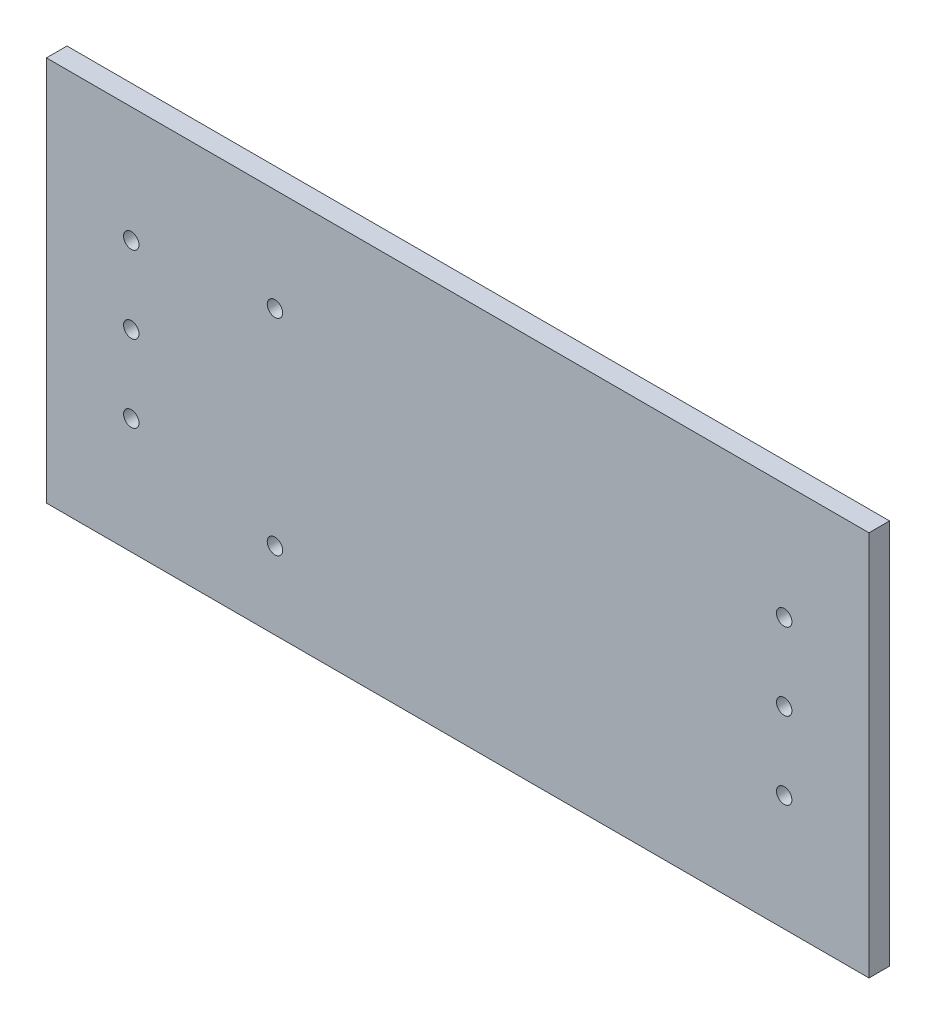
SolidWorks part; units mm, degrees
ref_plane "Front Plane" through (0, 0, 0) normal (0, 0, 1) x (1, 0, 0)
ref_plane "Top Plane" through (0, 0, 0) normal (0, 1, 0) x (1, 0, 0)
ref_plane "Right Plane" through (0, 0, 0) normal (1, 0, 0) x (0, 0, -1)
sketch "Sketch1" plane through (0, 0, 0) normal (0, 0, 1) x (1, 0, 0)
  line L1 (0, 0) -> (160, 0)
  line L2 (0, 0) -> (0, 75)
  line L3 (0, 75) -> (160, 75)
  line L4 (160, 0) -> (160, 75)
  dimension "D1" = 160
  dimension "D2" = 75
extrude "Boss-Extrude1" add sketch "Sketch1" along normal blind 4 contours L3 L4 L1 L2
hole_wizard "Ø3.0mm Dowel Hole1" positions "Sketch2" profile "Sketch3" hole size "Ø3.0" standard "ANSI Metric" end condition through all
sketch "Sketch2" plane through (0, 0, 4) normal (0, 0, 1) x (1, 0, 0)
  line L2 (0, 75) -> (160, 75) construction
  line L4 (0, 0) -> (0, 75) construction
  line L5 (0, 0) -> (160, 0) construction
  point P0 (16.5, 52.5)
  point P2 (16.5, 22.5)
  point P4 (143.5, 52.5)
  point P6 (143.5, 22.5)
  dimension "D1" = 127
  dimension "D2" = 127
  dimension "D3" = 16.5
  dimension "D4" = 16.5
  dimension "D5" = 22.5
  dimension "D6" = 22.5
  dimension "D8" = 22.5
sketch "Sketch3" plane through (16.5, 52.5, 4) normal (1, 0, 0) x (0, -1, 0)
  line L0 (0, 0) -> (0, 4)
  line L1 (0, 4) -> (1.5, 4)
  line L2 (1.5, 4) -> (1.5, 0)
  line L5 (1.5, 0) -> (0, 0)
  line L11 (0, -6.35) -> (0, 107.95) construction
  dimension "Thru Hole Dia." = 3
  dimension "Thru Hole Depth" = 4
hole_wizard "Ø3.0mm Dowel Hole2" positions "Sketch4" profile "Sketch5" hole size "Ø3.0" standard "ANSI Metric" end condition through all
sketch "Sketch4" plane through (0, 0, 4) normal (0, 0, 1) x (1, 0, 0)
  line L0 (0, 75) -> (160, 75) construction
  line L1 (0, 0) -> (0, 75) construction
  point P0 (16.5, 37.5)
  point P2 (143.5, 37.5)
  dimension "D1" = 37.5
  dimension "D2" = 37.5
  dimension "D3" = 127
  dimension "D4" = 16.5
sketch "Sketch5" plane through (16.5, 37.5, 4) normal (1, 0, 0) x (0, -1, 0)
  line L0 (0, 0) -> (0, 4)
  line L1 (0, 4) -> (1.5, 4)
  line L2 (1.5, 4) -> (1.5, 0)
  line L5 (1.5, 0) -> (0, 0)
  line L11 (0, -6.35) -> (0, 107.95) construction
  dimension "Thru Hole Dia." = 3
  dimension "Thru Hole Depth" = 4
hole_wizard "Ø3.0mm Press Dowel Hole1" positions "Sketch6" profile "Sketch7" hole size "Ø3.0" standard "AS"
sketch "Sketch6" plane through (0, 0, 4) normal (0, 0, 1) x (1, 0, 0)
  line L0 (0, 75) -> (160, 75) construction
  point P0 (44.4469, 15)
  point P2 (44.4469, 55)
  dimension "D1" = 40
  dimension "D2" = 20
sketch "Sketch7" plane through (44.4469, 15, 4) normal (1, 0, 0) x (0, -1, 0)
  line L0 (0, 0) -> (0, 6.9013)
  line L1 (0, 6.9013) -> (1.5, 6)
  line L2 (1.5, 6) -> (1.5, 0)
  line L5 (1.5, 0) -> (0, 0)
  line L10 (0, 6.9013) -> (-1.5, 6) construction
  line L11 (0, -6.35) -> (0, 107.95) construction
  dimension "Hole Dia." = 3
  dimension "Hole Depth" = 6
  dimension "Drill Angle" = 118
